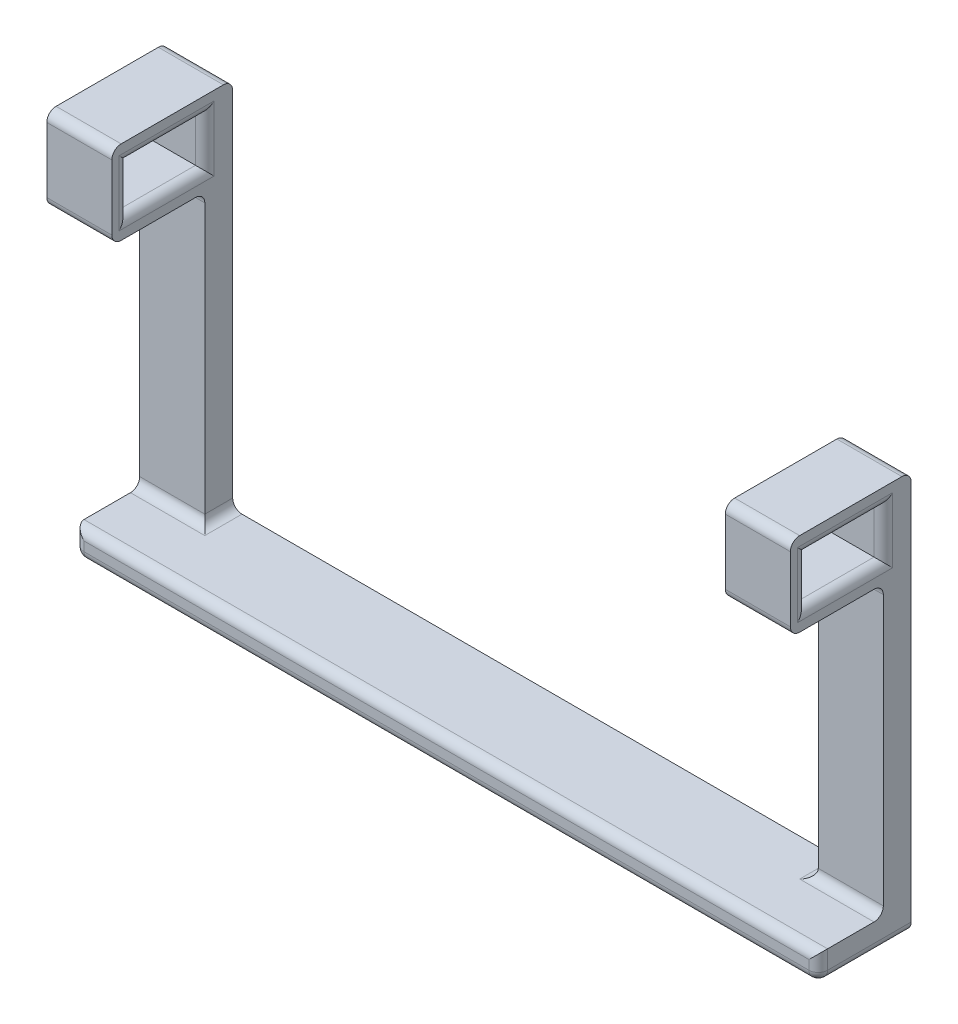
SolidWorks part; units mm, degrees
ref_plane "Front Plane" through (0, 0, 0) normal (0, 0, 1) x (1, 0, 0)
ref_plane "Top Plane" through (0, 0, 0) normal (0, 1, 0) x (1, 0, 0)
ref_plane "Right Plane" through (0, 0, 0) normal (1, 0, 0) x (0, 0, -1)
sketch "Sketch1" plane through (0, 0, 0) normal (0, 0, 1) x (1, 0, 0)
  line L0 (0, 0) -> (40, 0)
  line L1 (40, 0) -> (40, 43)
  line L2 (0, 0) -> (0, 3)
  line L3 (0, 3) -> (33, 3)
  line L4 (33, 3) -> (33, 43)
  line L5 (33, 43) -> (40, 43)
  dimension "D1" = 40
  dimension "D2" = 43
  dimension "D3" = 7
  dimension "D4" = 3
extrude "Boss-Extrude1" add sketch "Sketch1" along normal blind 13
sketch "Sketch2" plane through (40, 0, 0) normal (1, 0, 0) x (0, 0, -1)
  line L0 (-13, 43) -> (-13, 34)
  line L1 (-13, 0) -> (-13, 43) construction
  line L2 (-11.2294, 41) -> (-3, 41)
  line L3 (-3, 41) -> (-3, 36)
  line L4 (-3, 3) -> (-10, 3)
  line L5 (-10, 3) -> (-10, 0)
  line L6 (-13, 0) -> (0, 0) construction
  line L7 (-10, 0) -> (0, 0)
  line L8 (0, 0) -> (0, 43)
  line L9 (0, 43) -> (-13, 43)
  line L15 (-13, 0) -> (-10, 0)
  line L16 (-13, 34) -> (-3, 34)
  line L17 (-11.2294, 41) -> (-11.2294, 36)
  line L18 (-11.2294, 36) -> (-3, 36)
  line L19 (-3, 34) -> (-3, 3)
  line L20 (-13, 34) -> (-13, 0)
  dimension "D1" = 2
  dimension "D2" = 3
  dimension "D3" = 3
  dimension "D4" = 10
  dimension "D5" = 5
  dimension "D6" = 2
  dimension "D7" = 1.7706
extrude "Cut-Extrude1" cut sketch "Sketch2" against normal blind 100
mirror "Mirror2" about plane through (0, 0, 13) normal (1, 0, 0) of bodies 103
fillet "Fillet1" radius 1 30 edges at (36.5, 43, 13) (36.5, 34, 13) (33, 3, 1.5) (0, 3, 10) (33, 36, 7.1147) (33, 41, 7.1147) (33, 38.5, 11.2294) (40, 0, 5) (36.5, 3, 3) (36.5, 34, 3) (40, 1.5, 10) (0, 0, 10) (40, 41, 7.1147) (40, 38.5, 11.2294) (40, 36, 7.1147) (-40, 0, 5) (-40, 36, 7.1147) (-40, 38.5, 11.2294) (-33, 41, 7.1147) (36.5, 43, 0) (-33, 3, 1.5) (-36.5, 3, 3) (-36.5, 34, 13) (-36.5, 43, 13) (-36.5, 43, 0) (-36.5, 34, 3) (-40, 1.5, 10) (-33, 38.5, 11.2294) (-40, 41, 7.1147) (-33, 36, 7.1147)
